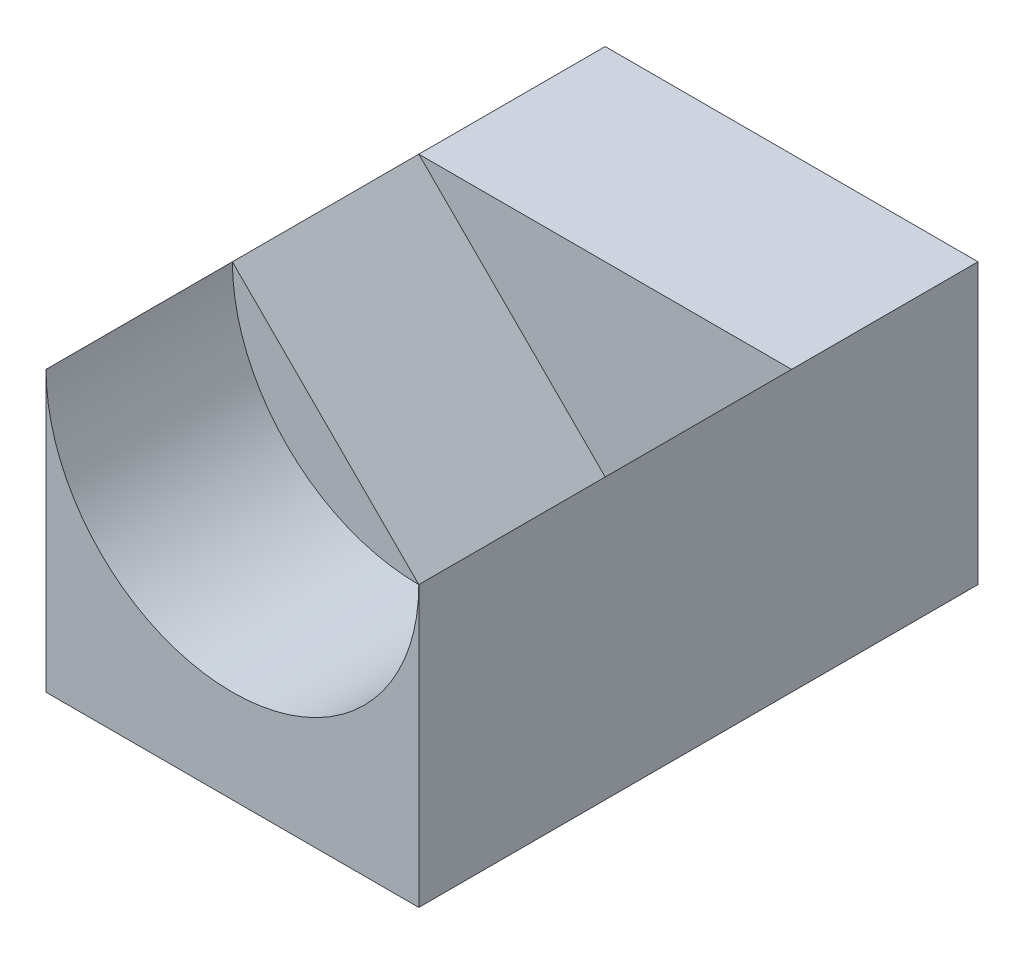
SolidWorks part; units mm, degrees
ref_plane "Front Plane" through (0, 0, 0) normal (0, 0, 1) x (1, 0, 0)
ref_plane "Top Plane" through (0, 0, 0) normal (0, 1, 0) x (1, 0, 0)
ref_plane "Right Plane" through (0, 0, 0) normal (1, 0, 0) x (0, 0, -1)
sketch "Sketch1" plane through (0, 0, 0) normal (0, 1, 0) x (1, 0, 0)
  line L1 (-20, 30) -> (20, 30)
  line L2 (-20, 30) -> (-20, -30)
  line L3 (-20, -30) -> (20, -30)
  line L4 (20, 30) -> (20, -30)
  line L5 (-20, 30) -> (20, -30) construction
  line L6 (-20, -30) -> (20, 30) construction
  point P0 (0, 0)
  dimension "D1" = 60
  dimension "D2" = 40
extrude "Boss-Extrude1" add sketch "Sketch1" along normal blind 30
sketch "Sketch2" plane through (0, 0, 30) normal (0, 0, 1) x (1, 0, 0)
  line L0 (-20, 30) -> (20, 30) construction
  line L1 (20, 30) -> (20, 0) construction
  line L2 (-20, 30) -> (20, 30)
  arc A0 (-20, 30) -> (20, 30) centre (0, 30) ccw
  point P9 (0, 30)
extrude "Cut-Extrude1" cut sketch "Sketch2" against normal blind 20 contours A0 L2
sketch "Sketch3" plane through (0, 0, 10) normal (0, 0, 1) x (1, 0, 0)
  line L0 (-20, 30) -> (0, 10)
  line L1 (0, 10) -> (20, 30)
  line L2 (-20, 30) -> (20, 30) construction
  line L3 (20, 30) -> (-20, 30)
  arc A0 (-20, 30) -> (20, 30) centre (0, 30) ccw construction
extrude "Cut-Extrude2" cut sketch "Sketch3" against normal blind 20
